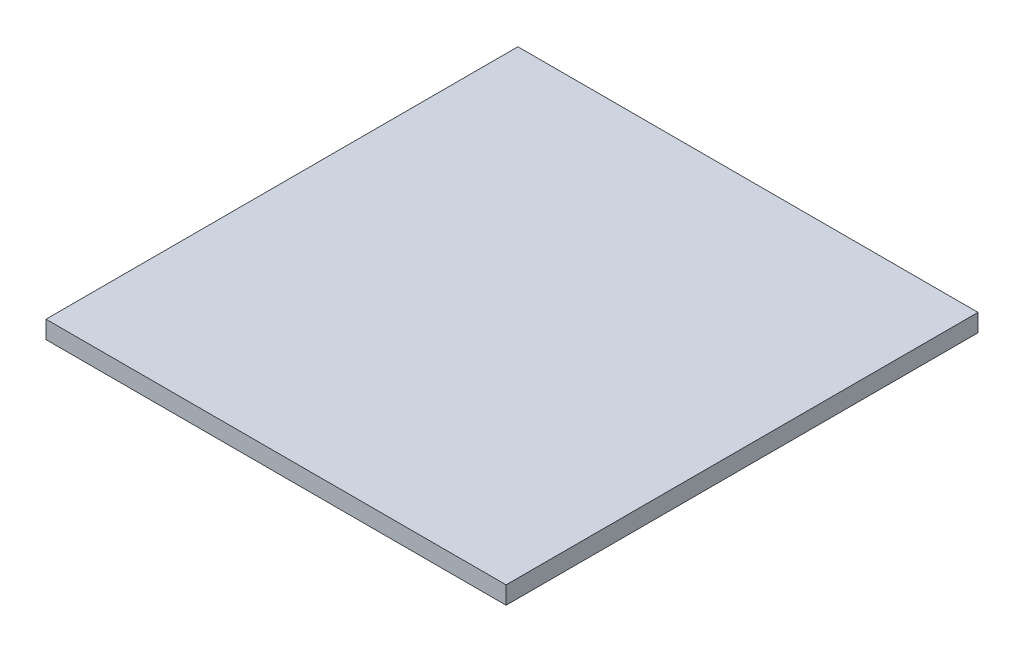
SolidWorks part; units mm, degrees
ref_plane "Front" through (0, 0, 0) normal (0, 0, 1) x (1, 0, 0)
ref_plane "Top" through (0, 0, 0) normal (0, 1, 0) x (1, 0, 0)
ref_plane "Right" through (0, 0, 0) normal (1, 0, 0) x (0, 0, -1)
sketch "Sketch1" plane through (0, 0, 0) normal (0, 1, 0) x (1, 0, 0)
  line L1 (-247.65, 254) -> (247.65, 254)
  line L2 (-247.65, 254) -> (-247.65, -254)
  line L3 (-247.65, -254) -> (247.65, -254)
  line L4 (247.65, 254) -> (247.65, -254)
  line L5 (-247.65, 254) -> (247.65, -254) construction
  line L6 (-247.65, -254) -> (247.65, 254) construction
  point P0 (0, 0)
  dimension "D1" = 495.3
  dimension "D2" = 508
extrude "Boss-Extrude1" add sketch "Sketch1" along normal blind 19.05
sketch "Sketch2" [suppressed] plane through (0, 19.05, 0) normal (0, 1, 0) x (1, 0, 0)
  line L0 (-254, 254) -> (-254, 215.9) construction
  line L1 (-254, 254) -> (-254, -254) construction
  line L2 (-254, 215.9) -> (-215.9, 215.9) construction
  line L3 (-215.9, 215.9) -> (-215.9, 254) construction
  line L4 (254, 254) -> (-254, 254) construction
  line L5 (-215.9, 254) -> (-254, 254) construction
  line L7 (-241.3, 241.3) -> (-190.5, 241.3)
  line L8 (-241.3, 241.3) -> (-241.3, 190.5)
  line L9 (-241.3, 190.5) -> (-190.5, 190.5)
  line L10 (-190.5, 241.3) -> (-190.5, 190.5)
  line L11 (-241.3, 241.3) -> (-190.5, 190.5) construction
  line L12 (-241.3, 190.5) -> (-190.5, 241.3) construction
  dimension "D1" = 50.8
  dimension "D2" = 50.8
  dimension "D3" = 12.7
extrude "Cut-Extrude1" [suppressed] cut sketch "Sketch2" against normal through all
pattern_linear "LPattern1" [suppressed] count 8 spacing 60.325 count 8 spacing 60.325
